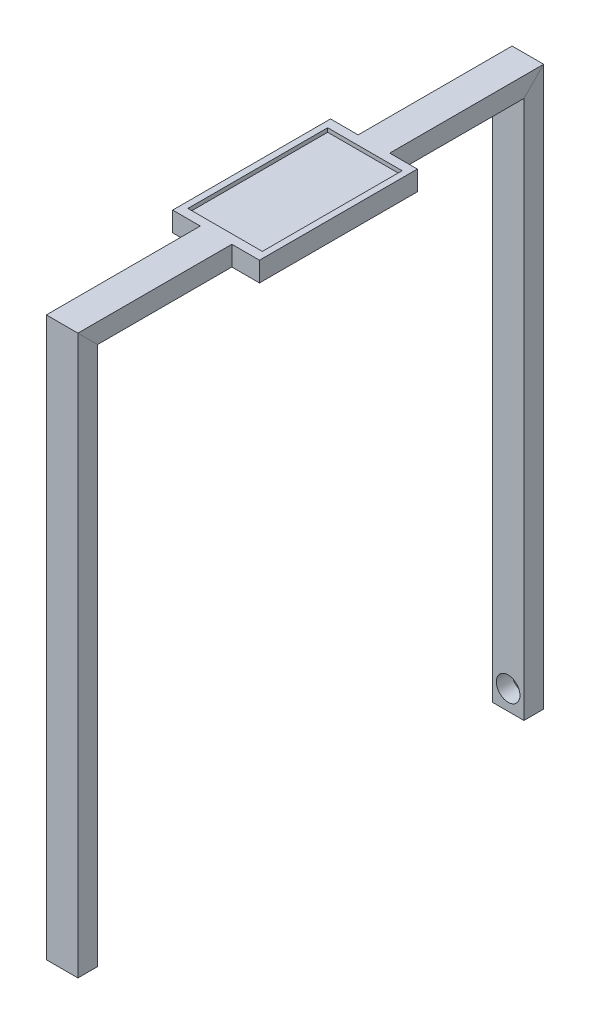
SolidWorks part; units mm, degrees
material "PE High Density"
ref_plane "Front Plane" through (0, 0, 0) normal (0, 0, 1) x (1, 0, 0)
ref_plane "Top Plane" through (0, 0, 0) normal (0, 1, 0) x (1, 0, 0)
ref_plane "Right Plane" through (0, 0, 0) normal (1, 0, 0) x (0, 0, -1)
sketch "Sketch2" plane through (0, 0, 0) normal (1, 0, 0) x (0, 0, -1)
  line L0 (-282.5, 0) -> (-282.5, 695)
  line L1 (-282.5, 695) -> (282.5, 695)
  line L2 (282.5, 695) -> (282.5, 0)
  point P2 (0, 695)
  dimension "D1" = 695
  dimension "D2" = 565
sketch "Sketch3" plane through (0, 0, 0) normal (0, 1, 0) x (1, 0, 0)
  line L0 (0, -282.5) -> (0, 282.5) construction
  line L1 (-20, -295) -> (20, -295)
  line L2 (-20, -295) -> (-20, -270)
  line L3 (-20, -270) -> (20, -270)
  line L4 (20, -295) -> (20, -270)
  line L5 (-20, -295) -> (20, -270) construction
  line L6 (-20, -270) -> (20, -295) construction
  point P0 (0, -282.5)
  dimension "D1" = 40
  dimension "D2" = 25
sweep "Sweep1" add profiles "Sketch3" path "Sketch2"
sketch "Sketch4" plane through (0, 0, 0) normal (0, 0, 1) x (1, 0, 0)
  line L0 (-20, 0) -> (20, 0) construction
  circle A0 centre (0, 25) radius 15
  dimension "D1" = 30
  dimension "D2" = 25
extrude "Cut-Extrude1" cut sketch "Sketch4" against normal blind 290 and the other way blind 290
sketch "Sketch5" plane through (0, 707.5, 0) normal (0, 1, 0) x (1, 0, 0)
  line L1 (-55, -100) -> (55, -100)
  line L2 (-55, -100) -> (-55, 100)
  line L3 (-55, 100) -> (55, 100)
  line L4 (55, -100) -> (55, 100)
  line L5 (-55, -100) -> (55, 100) construction
  line L6 (-55, 100) -> (55, -100) construction
  point P0 (0, 0)
  dimension "D1" = 200
  dimension "D2" = 110
extrude "Boss-Extrude1" add sketch "Sketch5" against normal blind 25
sketch "Sketch6" plane through (0, 707.5, 0) normal (0, 1, 0) x (1, 0, 0)
  line L1 (-47.1518, -88.535) -> (47.1518, -88.535)
  line L2 (-47.1518, -88.535) -> (-47.1518, 88.535)
  line L3 (-47.1518, 88.535) -> (47.1518, 88.535)
  line L4 (47.1518, -88.535) -> (47.1518, 88.535)
  line L5 (-47.1518, -88.535) -> (47.1518, 88.535) construction
  line L6 (-47.1518, 88.535) -> (47.1518, -88.535) construction
  point P0 (0, 0)
extrude "Cut-Extrude2" cut sketch "Sketch6" against normal blind 5
